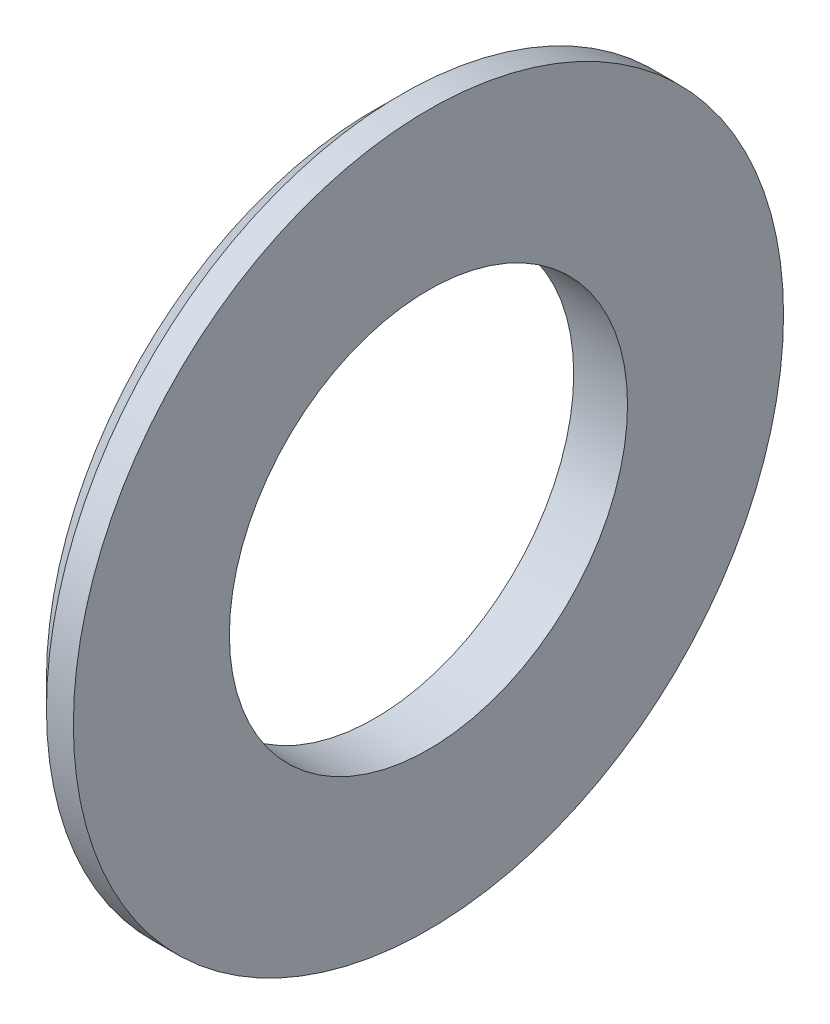
SolidWorks part; units mm, degrees
ref_plane "Plane1" through (0, 0, 0) normal (0, 0, 1) x (1, 0, 0)
ref_plane "Plane2" through (0, 0, 0) normal (0, 1, 0) x (1, 0, 0)
ref_plane "Plane3" through (0, 0, 0) normal (1, 0, 0) x (0, 0, -1)
sketch "Sketch1" plane through (0, 0, 0) normal (0, 0, 1) x (1, 0, 0)
  line L0 (-34.925, 0) -> (9.525, 0) construction
  line L1 (0, 18.5) -> (0, 33)
  line L2 (0, 33) -> (-2.5, 33)
  line L3 (-5, 30.5) -> (-5, 18.5)
  line L4 (-5, 18.5) -> (0, 18.5)
  line L5 (-5, 30.5) -> (-2.5, 33)
  dimension "Inside_dia" = 37
  dimension "Outside_dia" = 66
  dimension "Thickness" = 5
  dimension "D2" = 45
  dimension "D3" = 2.5
revolve "Base-Revolve" add sketch "Sketch1" angle 360 about L0
equation "\"D3@Sketch1\" = \"Thickness@Sketch1\" * .5"
